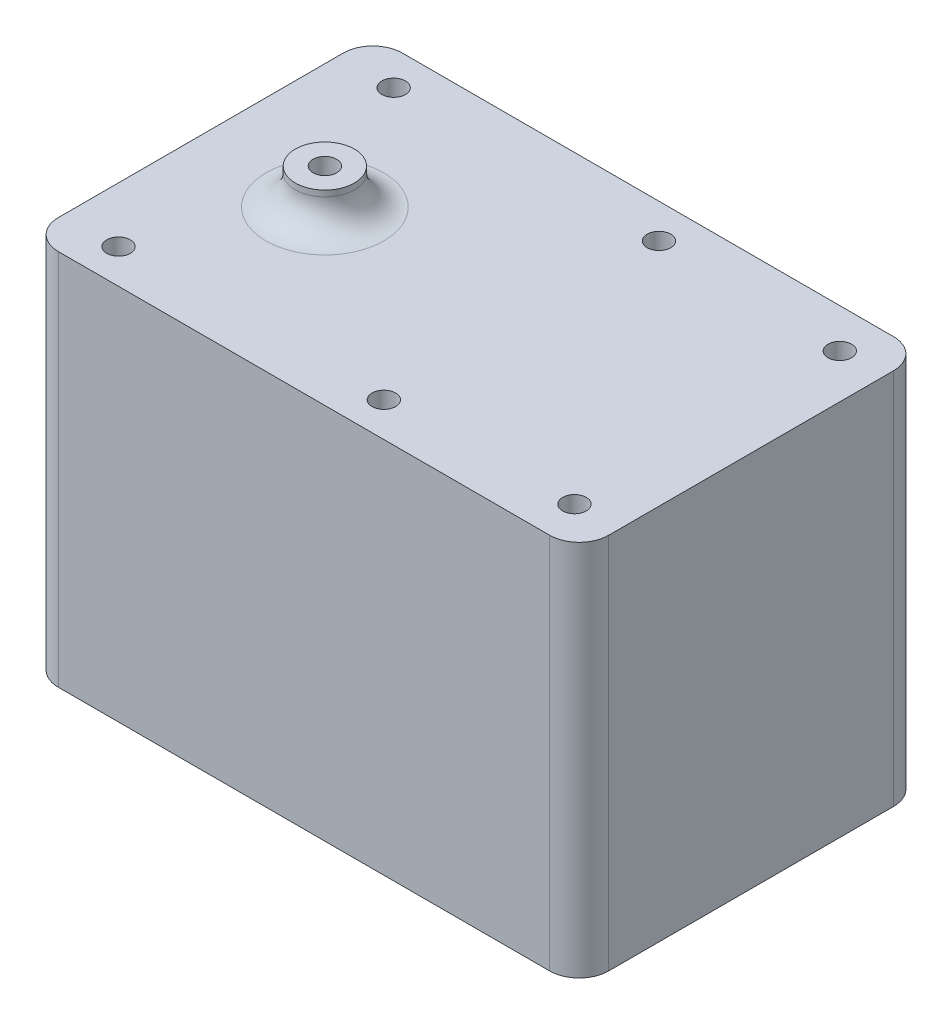
SolidWorks part; units mm, degrees
ref_plane "Front Plane" through (0, 0, 0) normal (0, 0, 1) x (1, 0, 0)
ref_plane "Top Plane" through (0, 0, 0) normal (0, 1, 0) x (1, 0, 0)
ref_plane "Right Plane" through (0, 0, 0) normal (1, 0, 0) x (0, 0, -1)
sketch "Sketch1" plane through (0, 0, 0) normal (0, 1, 0) x (1, 0, 0)
  line L0 (-22.38, 14) -> (-22.38, -14) construction
  line L1 (28, -17.5) -> (-28, -17.5)
  line L2 (28, -17.5) -> (28, 17.5)
  line L3 (28, 17.5) -> (-28, 17.5)
  line L4 (-28, -17.5) -> (-28, 17.5)
  line L5 (28, -17.5) -> (-28, 17.5) construction
  line L6 (28, 17.5) -> (-28, -17.5) construction
  line L7 (4.62, 14) -> (4.62, -14) construction
  line L8 (23.52, 13.5) -> (23.52, -13.5) construction
  line L9 (-28, 0) -> (28, 0) construction
  circle A0 centre (-22.38, 14) radius 1.2
  circle A1 centre (4.62, 14) radius 1.2
  circle A2 centre (-22.38, -14) radius 1.2
  circle A3 centre (4.62, -14) radius 1.2
  circle A4 centre (23.52, 13.5) radius 1.2
  circle A5 centre (23.52, -13.5) radius 1.2
  point P0 (0, 0)
  point P20 (-22.38, 0)
  point P21 (23.52, 0)
  dimension "D3" = 2.4
  dimension "D1" = 56
  dimension "D2" = 35
  dimension "D4" = 28
  dimension "D5" = 27
  dimension "D6" = 18.9
  dimension "D7" = 0.5
  dimension "D8" = 5.62
extrude "Boss-Extrude1" add sketch "Sketch1" along normal blind 38.4
sketch "Sketch2" plane through (0, 0, 0) normal (0, -1, 0) x (1, 0, 0)
  circle A0 centre (-15.38, 0) radius 1.2
  circle A1 centre (-22.38, 14) radius 1.2 construction
  circle A2 centre (-22.38, 14) radius 1.2 construction
  circle A3 centre (-15.38, 0) radius 3
  dimension "D1" = 2.4
  dimension "D3" = 6
  dimension "D2" = 7
extrude "Boss-Extrude2" add sketch "Sketch2" along normal blind 3.6
ref_plane "Plane1" through (0, 19.2, 0) normal (0, -1, 0) x (-1, 0, 0)
mirror "Mirror2" about plane through (0, 19.2, 0) normal (0, -1, 0) of "Boss-Extrude2"
fillet "Fillet2" radius 3 6 edges at (-15.38, 0, 3) (-15.38, 38.4, 3) (28, 19.2, -17.5) (28, 19.2, 17.5) (-28, 19.2, -17.5) (-28, 19.2, 17.5)
